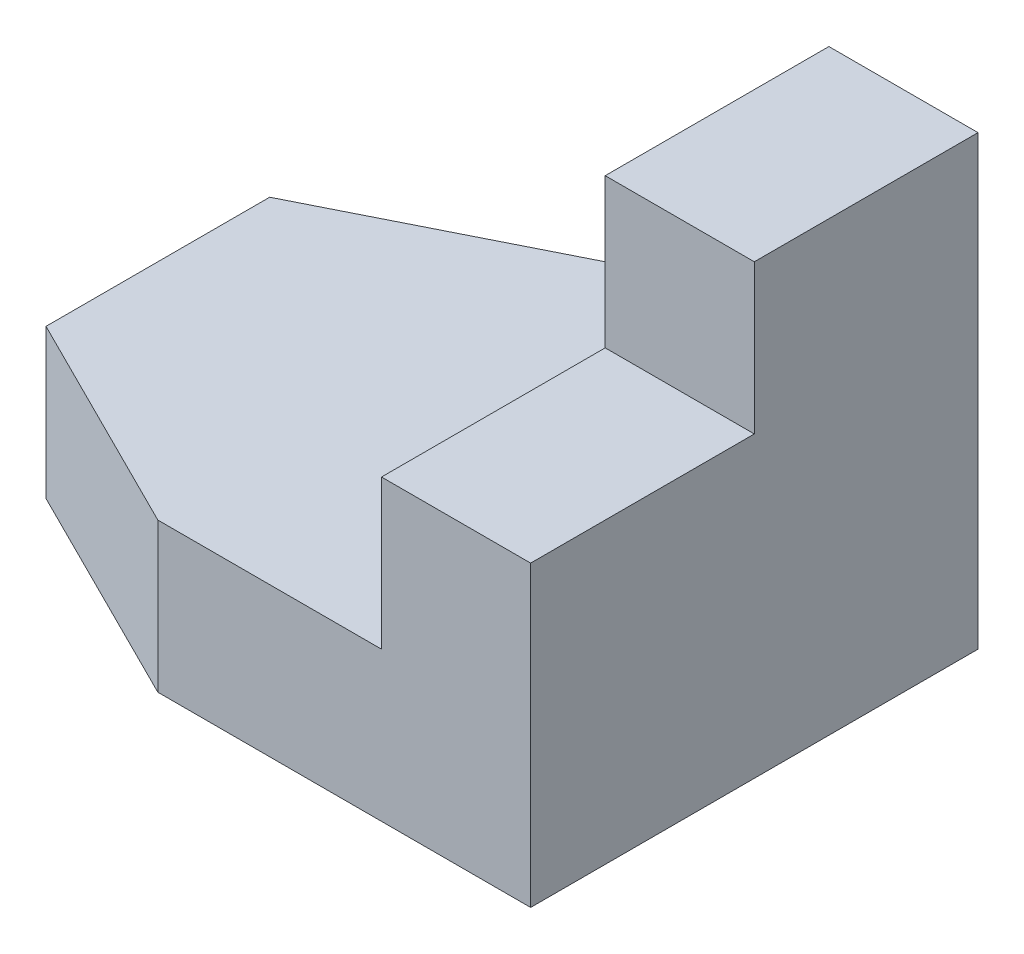
SolidWorks part; units mm, degrees
ref_plane "Ön Düzlem" through (0, 0, 0) normal (0, 0, 1) x (1, 0, 0)
ref_plane "Üst Düzlem" through (0, 0, 0) normal (0, 1, 0) x (1, 0, 0)
ref_plane "Sağ Düzlem" through (0, 0, 0) normal (1, 0, 0) x (0, 0, -1)
sketch "Çizim2" plane through (0, 0, 0) normal (0, 0, 1) x (1, 0, 0)
  line L0 (0, 0) -> (0, 30)
  line L1 (0, 30) -> (-10, 30)
  line L2 (-10, 30) -> (-10, 10)
  line L3 (-10, 10) -> (-40, 10)
  line L4 (-40, 10) -> (-40, 0)
  line L5 (-40, 0) -> (0, 0)
  dimension "D1" = 10
  dimension "D2" = 10
  dimension "D3" = 40
  dimension "D4" = 30
extrude "Yükseklik-Ekstrüzyon1" add sketch "Çizim2" along normal mid plane 30 contours L0 L1 L2 L3 L4 L5
sketch "Çizim3" plane through (0, 0, 0) normal (0, 1, 0) x (1, 0, 0)
  line L0 (-42.0589, 0) -> (1.5915, 0) construction
  line L1 (-40, 15) -> (-25, 15)
  line L2 (-10, 15) -> (-40, 15) construction
  line L3 (-25, 15) -> (-40, 7.5)
  line L4 (-40, -15) -> (-40, 15) construction
  line L5 (-40, 7.5) -> (-40, 15)
  line L6 (-25, -15) -> (-40, -7.5)
  line L7 (-40, -7.5) -> (-40, -15)
  line L8 (-40, -15) -> (-25, -15)
  dimension "D1" = 15
  dimension "D2" = 7.5
extrude "Kes-Ekstrüzyon1" cut sketch "Çizim3" along normal up to surface (10 mm away) up to face at (-25, 10, 0)
sketch "Çizim4" plane through (-10, 0, 0) normal (-1, 0, 0) x (0, 0, 1)
  line L1 (15, 30) -> (0, 30)
  line L2 (15, 30) -> (15, 20)
  line L3 (15, 20) -> (0, 20)
  line L4 (0, 30) -> (0, 20)
  dimension "D1" = 15
  dimension "D2" = 10
extrude "Kes-Ekstrüzyon2" cut sketch "Çizim4" against normal up to surface (10 mm away) up to face at (0, 15, 0)
